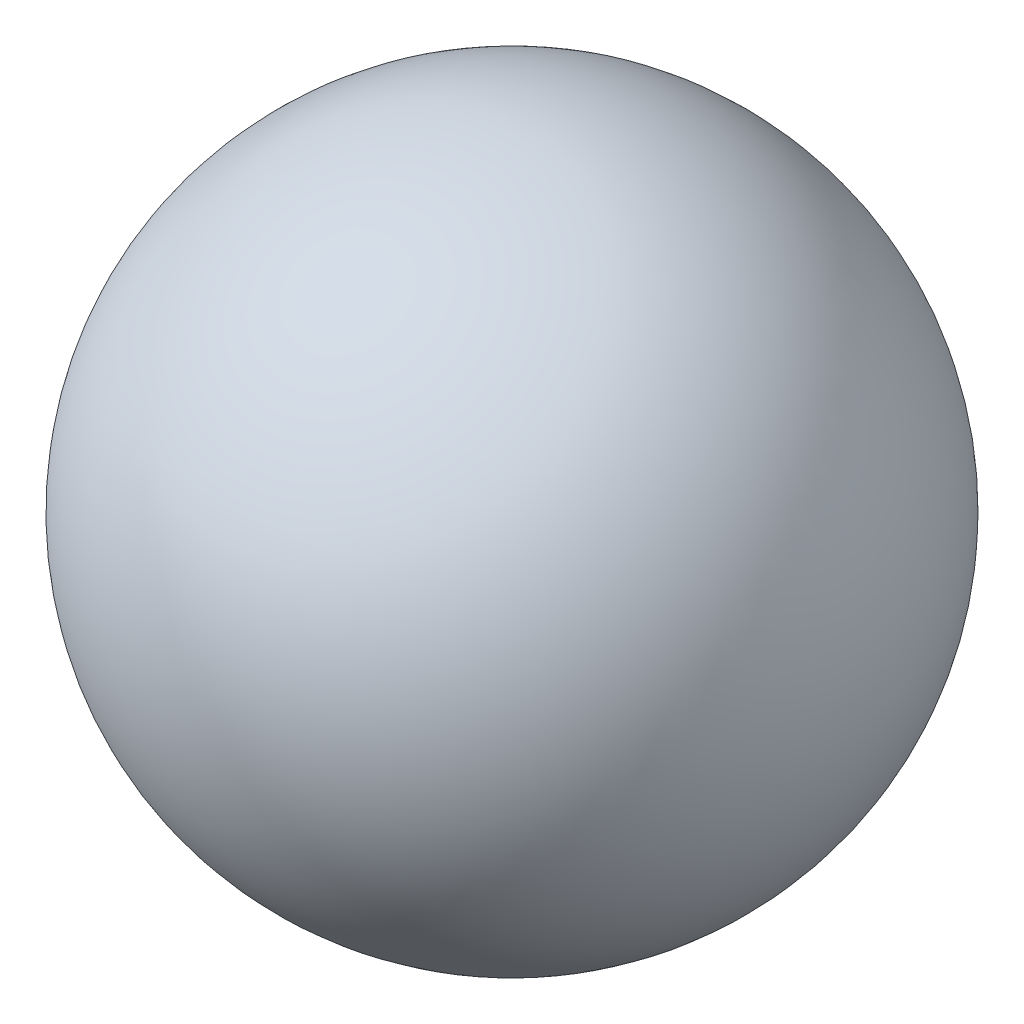
SolidWorks part; units mm, degrees
ref_plane "Alzado" through (0, 0, 0) normal (0, 0, 1) x (1, 0, 0)
ref_plane "Planta" through (0, 0, 0) normal (0, 1, 0) x (1, 0, 0)
ref_plane "Vista lateral" through (0, 0, 0) normal (1, 0, 0) x (0, 0, -1)
sketch "Croquis1" plane through (0, 0, 0) normal (0, 0, 1) x (1, 0, 0)
  line L0 (0, -55) -> (0, 55) construction
  line L1 (0, -43.6293) -> (0, 43.6293)
  arc A0 (0, 43.6293) -> (0, -43.6293) centre (0, 0) cw
revolve "Revolución1" add sketch "Croquis1" angle 360 about L1
sketch "Croquis2" plane through (0, 0, 0) normal (0, 0, 1) x (1, 0, 0)
  line L1 (0, 0) -> (5, 0)
  line L2 (0, 0) -> (0, -60)
  line L3 (0, -60) -> (5, -60)
  line L4 (5, 0) -> (5, -60)
  dimension "D1" = 5
  dimension "D2" = 60
revolve "Cortar-Revolución1" cut sketch "Croquis2" angle 360 about L2
